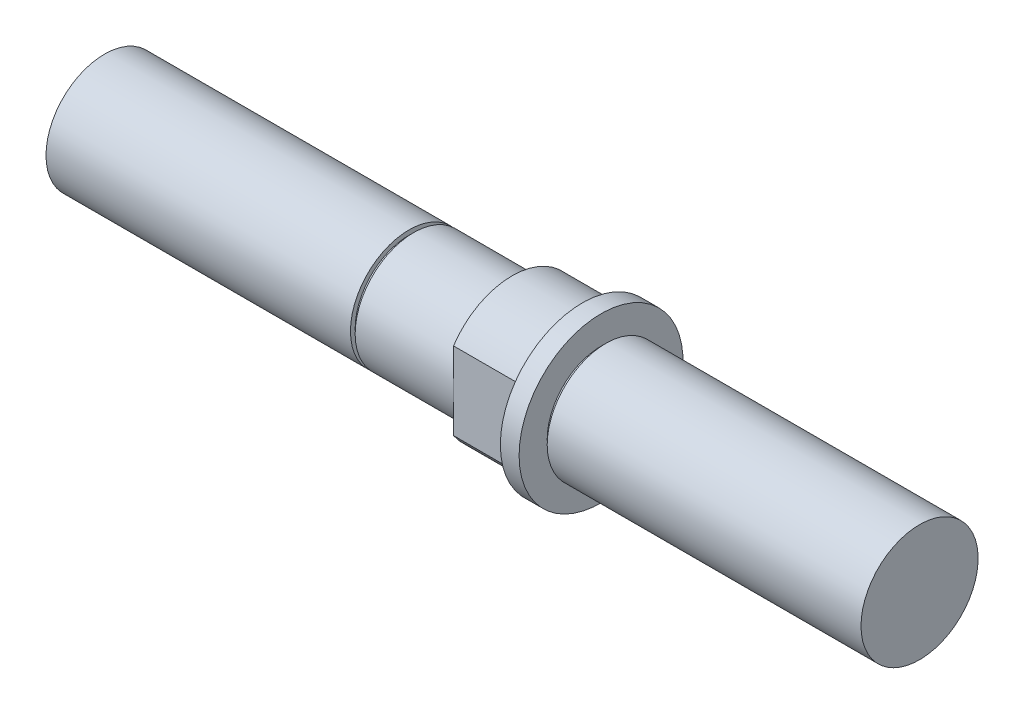
SolidWorks part; units mm, degrees
material "Alloy Steel"
ref_plane "Front Plane" through (0, 0, 0) normal (0, 0, 1) x (1, 0, 0)
ref_plane "Top Plane" through (0, 0, 0) normal (0, 1, 0) x (1, 0, 0)
ref_plane "Right Plane" through (0, 0, 0) normal (1, 0, 0) x (0, 0, -1)
sketch "Sketch3" plane through (0, 0, 0) normal (0, 0, 1) x (1, 0, 0)
  line L0 (0, 0) -> (0, 12.5)
  line L1 (0, 12.5) -> (-68, 12.5)
  line L2 (-68, 12.5) -> (-68, 17.5)
  line L3 (-68, 17.5) -> (-72, 17.5)
  line L4 (-72, 17.5) -> (-72, 15)
  line L5 (-72, 15) -> (-87, 15)
  line L6 (-87, 15) -> (-87, 12.5)
  line L7 (-87, 12.5) -> (-174, 12.5)
  line L8 (-174, 12.5) -> (-174, 0)
  line L9 (-174, 0) -> (0, 0) construction
  line L10 (0, 0) -> (-174, 0)
  dimension "D1" = 25
  dimension "D2" = 68
  dimension "D3" = 4
  dimension "D4" = 35
  dimension "D5" = 30
  dimension "D6" = 15
  dimension "D7" = 25
  dimension "D8" = 87
revolve "Revolve2" add sketch "Sketch3" angle 360 about L9
sketch "Sketch4" plane through (0, 0, 0) normal (0, 0, 1) x (1, 0, 0)
  line L0 (-108, 12.5) -> (-108, 11.5)
  line L1 (-87, 12.5) -> (-174, 12.5) construction
  line L2 (-108, 11.5) -> (-109, 11.5)
  line L3 (-109, 11.5) -> (-109, 12.5)
  line L4 (-109, 12.5) -> (-108, 12.5)
  line L5 (-174, 0) -> (-4.0428, 0) construction
  line L6 (-174, 12.5) -> (-174, -12.5) construction
  line L7 (-68, 12.5) -> (-68, 11.5)
  line L8 (-68, -17.5) -> (-68, 17.5) construction
  line L9 (-68, 11.5) -> (-67, 11.5)
  line L10 (-67, 11.5) -> (-67, 12.5)
  line L11 (0, 12.5) -> (-68, 12.5) construction
  line L12 (-67, 12.5) -> (-68, 12.5)
  dimension "D1" = 23
  dimension "D2" = 65
  dimension "D3" = 1
  dimension "D4" = 23
  dimension "D5" = 1
revolve "Cut-Revolve1" cut sketch "Sketch4" angle 360 about L5
sketch "Sketch5" plane through (-87, 0, 0) normal (-1, 0, 0) x (0, 0, 1)
  line L0 (0, 0) -> (0, -12.5) construction
  line L1 (-12.5, 8.2916) -> (-12.5, -8.2916)
  line L2 (12.5, 8.2916) -> (12.5, -8.2916)
  circle A0 centre (0, 0) radius 12.5 construction
  arc A1 (-12.5, -8.2916) -> (12.5, -8.2916) centre (0, 0) ccw
  arc A2 (12.5, 8.2916) -> (-12.5, 8.2916) centre (0, 0) ccw
  point P7 (12.5, 0)
  dimension "D1" = 30
  dimension "D2" = 25
extrude "Cut-Extrude1" cut sketch "Sketch5" against normal up to surface (15 mm away) flip side to cut up to face at (-72, 0, 15)
